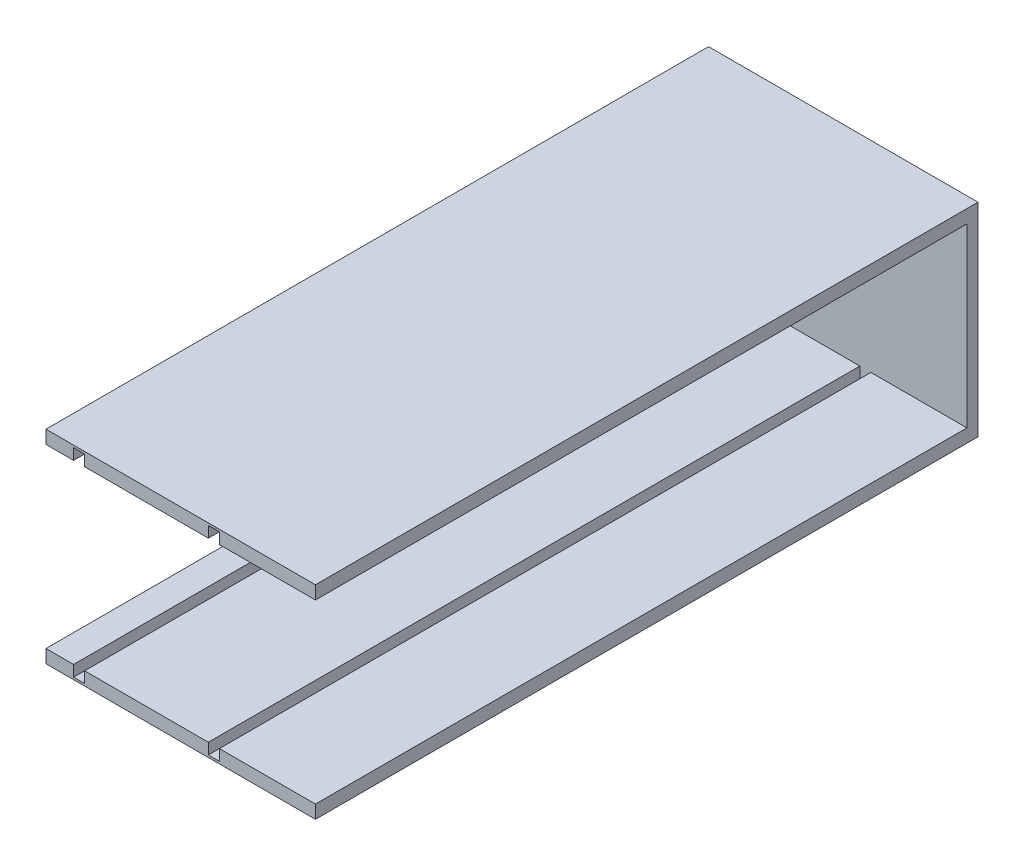
SolidWorks part; units mm, degrees
ref_plane "Front Plane" through (0, 0, 0) normal (0, 0, 1) x (1, 0, 0)
ref_plane "Top Plane" through (0, 0, 0) normal (0, 1, 0) x (1, 0, 0)
ref_plane "Right Plane" through (0, 0, 0) normal (1, 0, 0) x (0, 0, -1)
sketch "Sketch1" plane through (0, 0, 0) normal (0, 0, 1) x (1, 0, 0)
  line L0 (0, -30) -> (217.5, -30)
  line L1 (0, 0) -> (460, 0)
  line L4 (460, 0) -> (460, -30)
  line L5 (217.5, -30) -> (217.5, -5)
  line L6 (217.5, -5) -> (242.5, -5)
  line L7 (242.5, -5) -> (242.5, -30)
  line L8 (242.5, -30) -> (460, -30)
  line L22 (230, 0) -> (230, -460) construction
  line L23 (521.7993, -230) -> (-234.9328, -230) construction
  line L24 (-87.5, -5) -> (-87.5, -30)
  line L25 (-62.5, -5) -> (-87.5, -5)
  line L26 (-62.5, -30) -> (-62.5, -5)
  line L27 (-150, -30) -> (-87.5, -30)
  line L28 (-150, 0) -> (-150, -30)
  line L29 (0, 0) -> (-150, 0)
  line L31 (-62.5, -30) -> (0, -30)
  line L32 (-62.5, -430) -> (0, -430)
  line L33 (0, -460) -> (-150, -460)
  line L34 (-150, -460) -> (-150, -430)
  line L35 (-150, -430) -> (-87.5, -430)
  line L36 (-62.5, -430) -> (-62.5, -455)
  line L37 (-62.5, -455) -> (-87.5, -455)
  line L38 (-87.5, -455) -> (-87.5, -430)
  line L39 (242.5, -430) -> (460, -430)
  line L40 (242.5, -455) -> (242.5, -430)
  line L41 (217.5, -455) -> (242.5, -455)
  line L42 (217.5, -430) -> (217.5, -455)
  line L43 (460, -460) -> (460, -430)
  line L44 (0, -460) -> (460, -460)
  line L45 (0, -430) -> (217.5, -430)
  dimension "D1" = 460
  dimension "D2" = 460
  dimension "D3" = 25
  dimension "D4" = 217.5
  dimension "D5" = 25
  dimension "D6" = 25
  dimension "D7" = 5
extrude "Boss-Extrude1" add sketch "Sketch1" along normal blind 1500
sketch "Sketch5" plane through (0, 0, 0) normal (0, 0, -1) x (-1, 0, 0)
  line L1 (150, 0) -> (-460, 0)
  line L2 (150, 0) -> (150, -460)
  line L3 (150, -460) -> (-460, -460)
  line L4 (-460, 0) -> (-460, -460)
extrude "Boss-Extrude5" add sketch "Sketch5" against normal blind 25
